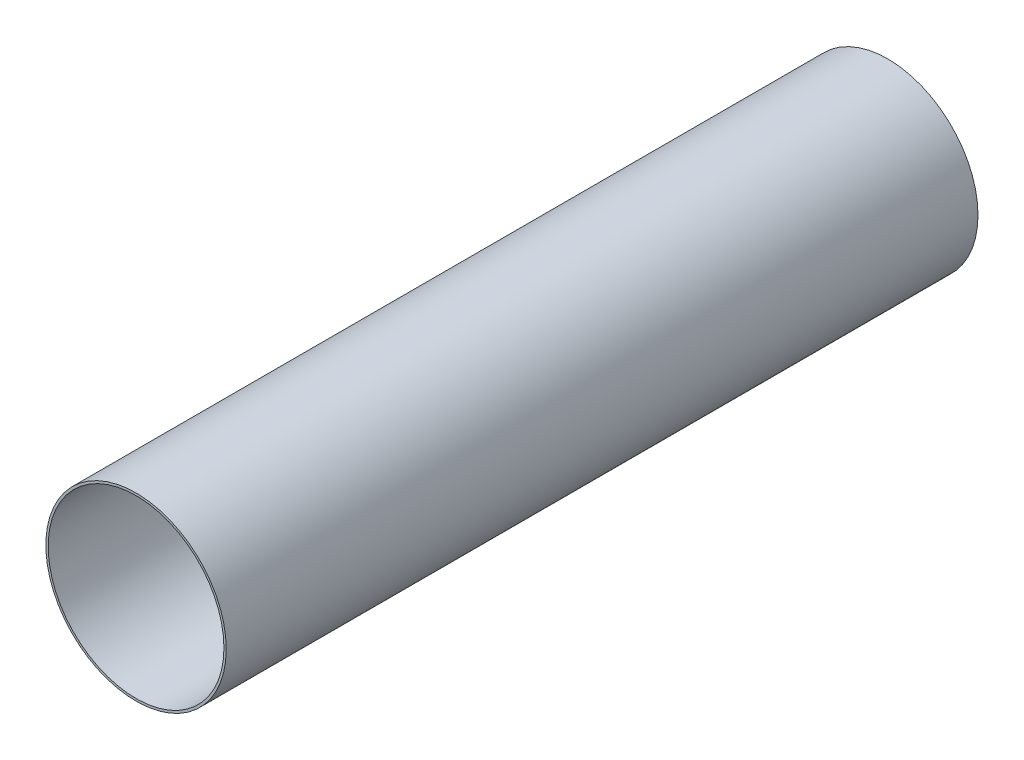
SolidWorks part; units mm, degrees
material "E-Glass Fiber"
ref_plane "Front" through (0, 0, 0) normal (0, 0, 1) x (1, 0, 0)
ref_plane "Top" through (0, 0, 0) normal (0, 1, 0) x (1, 0, 0)
ref_plane "Right" through (0, 0, 0) normal (1, 0, 0) x (0, 0, -1)
sketch "Sketch1" plane through (0, 0, 0) normal (0, 0, 1) x (1, 0, 0)
  circle A0 centre (0, 0) radius 78
  circle A1 centre (0, 0) radius 76
  dimension "D1" = 156
  dimension "D2" = 152
extrude "Boss-Extrude1" add sketch "Sketch1" along normal blind 650
